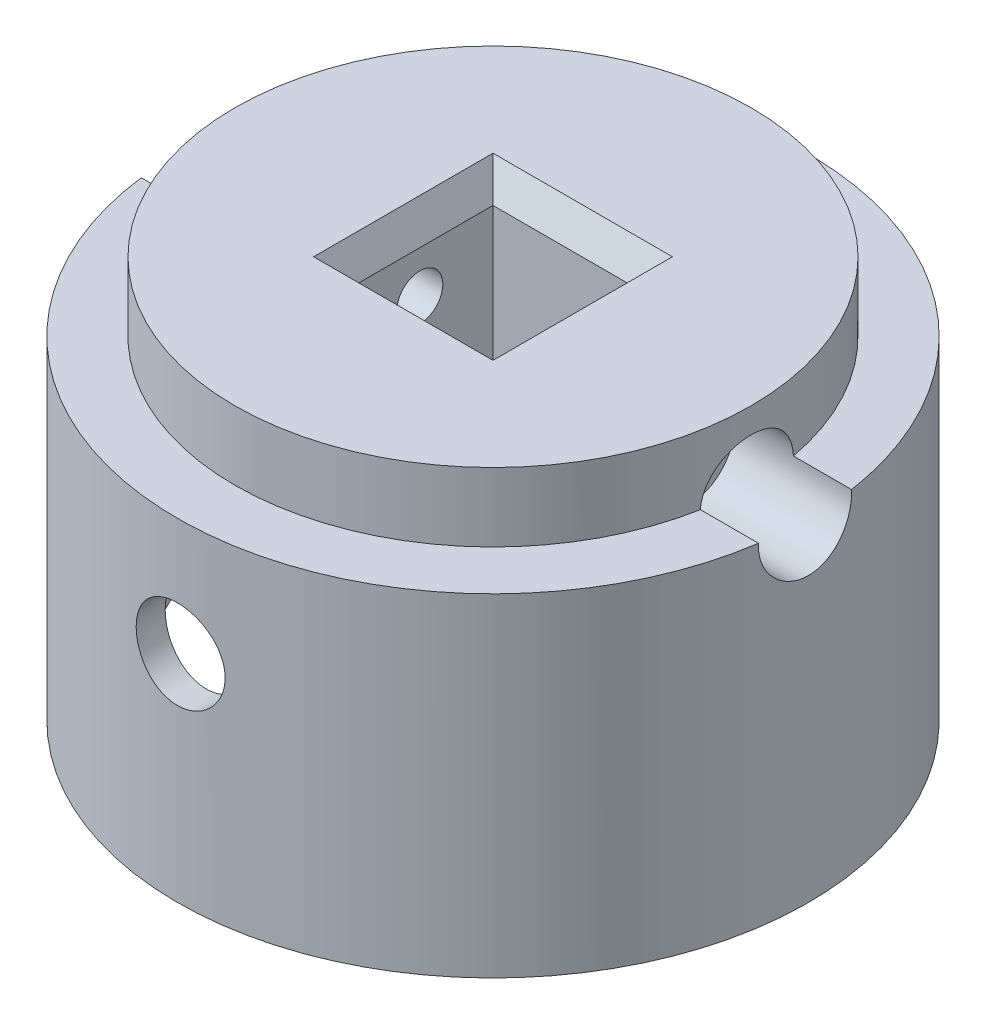
SolidWorks part; units mm, degrees
ref_plane "Спереди" through (0, 0, 0) normal (0, 0, 1) x (1, 0, 0)
ref_plane "Сверху" through (0, 0, 0) normal (0, 1, 0) x (1, 0, 0)
ref_plane "Справа" through (0, 0, 0) normal (1, 0, 0) x (0, 0, -1)
sketch "Sketch1" plane through (0, 0, 0) normal (0, 1, 0) x (1, 0, 0)
  circle A0 centre (0, 0) radius 22
  dimension "D1" = 44
extrude "Boss-Extrude1" add sketch "Sketch1" along normal blind 28
sketch "Sketch2" plane through (0, 0, 0) normal (0, -1, 0) x (1, 0, 0)
  line L1 (5.1, 5.1) -> (-5.1, 5.1)
  line L2 (5.1, 5.1) -> (5.1, -5.1)
  line L3 (5.1, -5.1) -> (-5.1, -5.1)
  line L4 (-5.1, 5.1) -> (-5.1, -5.1)
  line L5 (5.1, 5.1) -> (-5.1, -5.1) construction
  line L6 (5.1, -5.1) -> (-5.1, 5.1) construction
  point P0 (0, 0)
  dimension "D1" = 10.2
extrude "Cut-Extrude2" cut sketch "Sketch2" against normal through all
shell "Shell3" thickness 2
sketch "Sketch3" plane through (0, 0, 7.1) normal (0, 0, 1) x (1, 0, 0)
  line L0 (0, 26) -> (0, 0) construction
  line L1 (7.1, 26) -> (-7.1, 26) construction
  line L2 (7.1, 0) -> (-7.1, 0) construction
  line L3 (-22, 0) -> (22, 0) construction
  circle A0 centre (0, 15) radius 3.1
  point P8 (0, 0)
  point P9 (-2.0746, 13.4342)
  dimension "D1" = 6.2
  dimension "D2" = 15
extrude "Cut-Extrude3" cut sketch "Sketch3" along normal through all
chamfer "Chamfer1" distance 2 angle 30 4 edges at (-5.1, 28, 0) (0, 28, 5.1) (5.1, 28, 0) (0, 28, -5.1)
sketch "Sketch18" plane through (0, 26, 0) normal (0, -1, 0) x (1, 0, 0)
  line L0 (0, 0) -> (-17.9759, -8.7674) construction
  line L1 (0, 0) -> (-16.961, 10.5984) construction
  line L2 (0, 0) -> (0, -20) construction
  line L3 (-15.2795, -7.4523) -> (-17.9759, -8.7674)
  line L4 (-14.4168, 9.0086) -> (-16.961, 10.5984)
  circle A0 centre (0, 0) radius 20 construction
  arc A1 (-17.9759, -8.7674) -> (-16.961, 10.5984) centre (0, 0) cw
  arc A2 (-14.4168, 9.0086) -> (-15.2795, -7.4523) centre (0, 0) ccw
  dimension "D1" = 64
  dimension "D2" = 58
  dimension "D3" = 3
extrude "Boss-Extrude8" add sketch "Sketch18" along normal offset from surface (23 mm away) 3 up to face at (0, 0, 20)
sketch "Sketch9" plane through (0, 0, 0) normal (0, -1, 0) x (1, 0, 0)
  line L0 (0, -7.1) -> (0, -20) construction
  line L2 (1.9968, -21.9092) -> (-16.5692, -14.4727)
  line L3 (-16.5692, -14.4727) -> (-17.6847, -17.2577)
  line L4 (-17.6847, -17.2577) -> (0.8814, -24.6941)
  line L5 (0.8814, -24.6941) -> (1.9968, -21.9092)
  line L6 (-7.1, -7.1) -> (7.1, -7.1) construction
  line L7 (1.9968, -21.9092) -> (0, -7.1) construction
  circle A0 centre (0, 0) radius 22 construction
  circle A1 centre (0, 0) radius 20 construction
  dimension "D1" = 20
  dimension "D2" = 3
  dimension "D3" = 7.679
extrude "Boss-Extrude4" add sketch "Sketch9" against normal blind 20
sketch "Sketch11" plane through (0, 0, 0) normal (0, -1, 0) x (1, 0, 0)
  line L0 (1.9968, -21.9092) -> (7.1, -7.1)
  line L1 (7.1, -7.1) -> (-7.1, -7.1)
  line L2 (-7.1, -7.1) -> (-16.5692, -14.4727)
  line L3 (-16.5692, -14.4727) -> (1.9968, -21.9092) construction
  line L4 (-3.573, -19.6783) -> (-10.9994, -16.7037) construction
  arc A0 (1.9968, -21.9092) -> (-16.5692, -14.4727) centre (0, 0) ccw construction
  arc A1 (1.9968, -21.9092) -> (-16.5692, -14.4727) centre (0, 0) cw
  arc A2 (1.9968, -21.9092) -> (-16.5692, -14.4727) centre (0, 0) ccw construction
  point P4 (-7.2862, -18.191)
extrude "Boss-Extrude6" add sketch "Sketch11" against normal up to surface (26 mm away) up to face at (0, 26, 0)
sketch "Sketch12" plane through (0, 0, 0) normal (0, -1, 0) x (1, 0, 0)
  line L0 (-7.1, -7.1) -> (-14.9884, -13.2419) construction
  line L1 (2.7187, -19.8144) -> (7.1, -7.1) construction
  line L2 (3.8373, -16.5682) -> (2.7187, -19.8144)
  line L3 (-14.9884, -13.2419) -> (-12.6213, -11.3989)
  arc A0 (2.7187, -19.8144) -> (-14.9884, -13.2419) centre (0, 0) cw
  arc A1 (-12.6213, -11.3989) -> (3.8373, -16.5682) centre (0, 0) ccw
  arc A2 (2.7187, -19.8144) -> (-14.9884, -13.2419) centre (0, 0) ccw construction
  dimension "D1" = 3
extrude "Cut-Extrude5" cut sketch "Sketch12" against normal blind 10
sketch "Sketch13" plane through (-8.4017, 0, -20.9759) normal (-0.3718, 0, -0.9283) x (-0.9283, 0, 0.3718)
  line L0 (0, 20) -> (0, 0) construction
  line L1 (10, 20) -> (-10, 20) construction
  line L2 (10, 0) -> (-10, 0) construction
  circle A0 centre (0, 10) radius 3.8
  dimension "D1" = 7.6
extrude "Cut-Extrude6" cut sketch "Sketch13" against normal blind 16
sketch "Sketch15" plane through (-8.4017, 0, -20.9759) normal (-0.3718, 0, -0.9283) x (-0.9283, 0, 0.3718)
  line L0 (-10, 10) -> (10, 10) construction
  line L1 (-10, 20) -> (-10, 0) construction
  line L2 (10, 20) -> (10, 0) construction
  line L4 (5, 11.5) -> (-5, 11.5)
  line L5 (5, 11.5) -> (5, 8.5)
  line L6 (5, 8.5) -> (-5, 8.5)
  line L7 (-5, 11.5) -> (-5, 8.5)
  line L8 (5, 11.5) -> (-5, 8.5) construction
  line L9 (5, 8.5) -> (-5, 11.5) construction
  point P6 (0, 10)
  dimension "D1" = 10
  dimension "D2" = 3
extrude "Cut-Extrude8" cut sketch "Sketch15" against normal blind 16
sketch "Sketch17" plane through (0, 0, 0) normal (0, -1, 0) x (1, 0, 0)
  line L0 (7.1, 7.1) -> (7.1, -7.1)
  line L1 (7.1, -7.1) -> (3.8373, -16.5682)
  line L2 (7.1, 7.1) -> (-7.1, 7.1)
  line L3 (-7.1, 7.1) -> (-7.1, -7.1)
  line L4 (-7.1, -7.1) -> (-12.6213, -11.3989)
  arc A0 (3.8373, -16.5682) -> (-12.6213, -11.3989) centre (0, 0) cw
  arc A1 (-12.6213, -11.3989) -> (3.8373, -16.5682) centre (0, 0) ccw construction
extrude "Cut-Extrude9" cut sketch "Sketch17" against normal blind 2
sketch "Sketch20" plane through (0, 26, 0) normal (0, -1, 0) x (1, 0, 0)
  line L0 (2.7187, -19.8144) -> (7.1, -7.1)
  line L1 (7.1, -7.1) -> (7.1, 7.1)
  line L2 (7.1, 7.1) -> (-7.1, 7.1)
  line L3 (-7.1, 7.1) -> (-7.1, -7.1)
  line L4 (-7.1, -7.1) -> (-14.9884, -13.2419)
  arc A0 (2.7187, -19.8144) -> (-14.9884, -13.2419) centre (0, 0) ccw
  arc A1 (2.7187, -19.8144) -> (-16.961, 10.5984) centre (0, 0) ccw construction
extrude "Boss-Extrude10" add sketch "Sketch20" along normal blind 7
sketch "Sketch21" plane through (0, 28, 0) normal (0, 1, 0) x (1, 0, 0)
  circle A0 centre (0, 0) radius 18
  dimension "D1" = 36
extrude "Cut-Extrude11" cut sketch "Sketch21" against normal blind 4.8 flip side to cut
sketch "Sketch22" plane through (5.1, 0, 0) normal (-1, 0, 0) x (0, 0, 1)
  line L0 (0, 26) -> (0, 2) construction
  line L1 (5.1, 26) -> (-5.1, 26) construction
  line L2 (-5.1, 2) -> (5.1, 2) construction
  line L3 (-6.2547, 28) -> (6.2547, 28) construction
  circle A0 centre (0, 23) radius 1.6
  point P10 (0, 28)
  dimension "D1" = 3.2
  dimension "D2" = 5
extrude "Cut-Extrude12" cut sketch "Sketch22" against normal through all both and the other way through all
sketch "Sketch24" plane through (5.1, 0, 0) normal (-1, 0, 0) x (0, 0, 1)
  circle A0 centre (0, 23) radius 3.25
  dimension "D1" = 6.5
extrude "Cut-Extrude13" cut sketch "Sketch24" against normal through all from offset 8.5 offset against normal yes
sketch "Sketch25" plane through (-5.1, 0, 0) normal (1, 0, 0) x (0, 0, -1)
  line L0 (-5.1, 26) -> (-5.1, 2) construction
  line L1 (0, 19.8936) -> (2.6903, 21.4468)
  line L2 (2.6903, 21.4468) -> (2.6903, 24.5532)
  line L3 (2.6903, 24.5532) -> (0, 26.1064)
  line L4 (0, 26.1064) -> (-2.6903, 24.5532)
  line L5 (-2.6903, 24.5532) -> (-2.6903, 21.4468)
  line L6 (-2.6903, 21.4468) -> (0, 19.8936)
  circle A0 centre (0, 23) radius 3.1064 construction
extrude "Cut-Extrude14" cut sketch "Sketch25" against normal through all from offset 8.5
